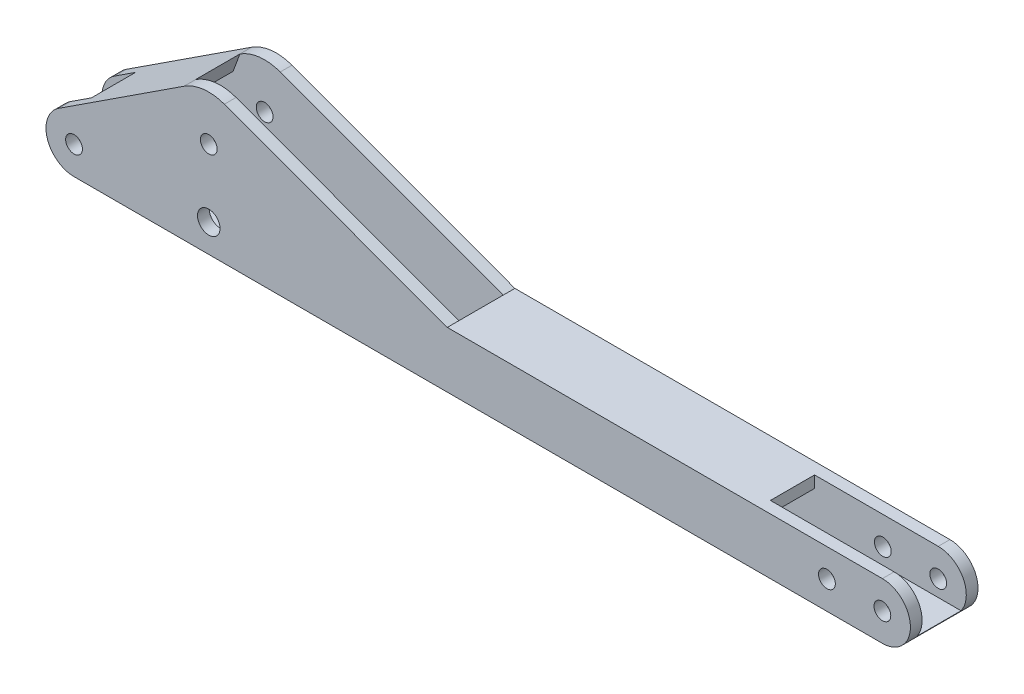
SolidWorks part; units mm, degrees
ref_plane "Front Plane" through (0, 0, 0) normal (0, 0, 1) x (1, 0, 0)
ref_plane "Top Plane" through (0, 0, 0) normal (0, 1, 0) x (1, 0, 0)
ref_plane "Right Plane" through (0, 0, 0) normal (1, 0, 0) x (0, 0, -1)
sketch "Sketch1" plane through (0, 0, 0) normal (0, 0, 1) x (1, 0, 0)
  line L0 (20.4249, 0) -> (3680.4249, 0)
  line L1 (-48.9901, 233.3512) -> (518.3771, 603.6692)
  line L2 (701.0552, 624.4483) -> (1710.4249, 254)
  line L3 (1710.4249, 254) -> (3680.4249, 254)
  arc A0 (20.4249, 0) -> (-48.9901, 233.3512) centre (20.4249, 127) cw
  arc A1 (518.3771, 603.6692) -> (701.0552, 624.4483) centre (630.4249, 432) cw
  circle A2 centre (20.4249, 127) radius 38
  circle A3 centre (630.4249, 127) radius 51
  circle A4 centre (630.4249, 432) radius 38
  arc A5 (3680.4249, 254) -> (3680.4249, 0) centre (3680.4249, 127) cw
  circle A6 centre (3680.4249, 127) radius 38
  circle A7 centre (3429.4249, 127) radius 38
  dimension "D2" = 127
  dimension "D3" = 76
  dimension "D4" = 102
  dimension "D5" = 76
  dimension "D8" = 205
  dimension "D6" = 305
  dimension "D7" = 127
  dimension "D9" = 254
  dimension "D10" = 251
  dimension "D11" = 1970
  dimension "D12" = 610
  dimension "D13" = 2799
extrude "Boss-Extrude1" add sketch "Sketch1" against normal blind 306
sketch "Sketch2" plane through (0, 254, 0) normal (0, 1, 0) x (1, 0, 0)
  line L0 (3680.4249, 306) -> (1710.4249, 306) construction
  line L1 (1710.4249, 306) -> (1710.4249, 0) construction
  line L2 (3120.4249, 306) -> (3680.4249, 306)
  line L3 (3120.4249, 306) -> (3120.4249, 0)
  line L4 (3120.4249, 0) -> (3680.4249, 0)
  line L5 (3680.4249, 306) -> (3680.4249, 0)
  line L6 (3807.4249, 0) -> (3807.4249, 306) construction
  line L7 (3680.4249, 253) -> (3807.4249, 253)
  line L8 (3680.4249, 253) -> (3680.4249, 53)
  line L9 (3680.4249, 53) -> (3807.4249, 53)
  line L10 (3807.4249, 253) -> (3807.4249, 53)
  line L17 (3120.4249, 253) -> (3680.4249, 253)
  line L18 (3120.4249, 53) -> (3680.4249, 53)
  dimension "D1" = 1410
  dimension "D2" = 53
  dimension "D3" = 53
sketch "Sketch3" plane through (0, 254, 0) normal (0, 1, 0) x (1, 0, 0)
sketch "Sketch8" plane through (285.1934, 777.0736, 0) normal (0.3445, 0.9388, 0) x (0.9388, -0.3445, 0)
  line L0 (278.6509, 253) -> (1518.1866, 253)
  line L1 (278.6509, 306) -> (1518.1866, 306)
  line L2 (278.6509, 306) -> (278.6509, 0)
  line L3 (278.6509, 0) -> (1518.1866, 0)
  line L4 (1518.1866, 306) -> (1518.1866, 0)
  line L5 (278.6509, 53) -> (1518.1866, 53)
  line M4 (442.9848, 306) -> (442.9848, 0)
  dimension "D1" = 53
  dimension "D2" = 53
extrude "Cut-Extrude5" cut sketch "Sketch8" against normal through all contours L5 L4 L0 M4 | L2 L5 L0 M4
sketch "Sketch9" plane through (0, 254, 0) normal (0, 1, 0) x (1, 0, 0)
extrude "Cut-Extrude10" cut sketch "Sketch2" against normal blind 201 contours L3 L18 L5 L17 | L10 L7 L5 L9
sketch "Sketch15" plane through (3120.4249, 0, 0) normal (1, 0, 0) x (0, 0, -1)
  line L0 (53, 201) -> (253, 201)
  line L1 (53, 254) -> (253, 254)
  line L2 (53, 254) -> (53, 53)
  line L3 (53, 53) -> (253, 53)
  line L4 (253, 254) -> (253, 53)
  line M3 (53, 254) -> (53, 53)
  line M4 (53, 53) -> (253, 53)
  line M5 (253, 53) -> (253, 254)
  dimension "D1" = 53
extrude "Cut-Extrude11" cut sketch "Sketch15" against normal through all contours L0 M3 M4 M5
sketch "Sketch16" plane through (0, 0, 0) normal (0, 0, 1) x (1, 0, 0)
  line L0 (-48.9901, 233.3512) -> (45.9249, 295.3017)
  line L1 (45.9249, 295.3017) -> (238.667, 0)
  line L2 (238.667, 0) -> (20.4249, 0)
  line L4 (20.4249, 0) -> (3680.4249, 0)
  line L5 (3680.4249, 254) -> (1710.4249, 254)
  line L6 (1710.4249, 254) -> (701.0552, 624.4483)
  line L7 (518.3771, 603.6692) -> (-48.9901, 233.3512)
  line L8 (20.4249, 0) -> (3680.4249, 0)
  line L9 (3680.4249, 254) -> (1710.4249, 254)
  line L10 (1710.4249, 254) -> (701.0552, 624.4483)
  line L11 (518.3771, 603.6692) -> (-48.9901, 233.3512)
  arc A3 (-48.9901, 233.3512) -> (20.4249, 0) centre (20.4249, 127) ccw
  arc A4 (3680.4249, 0) -> (3680.4249, 254) centre (3680.4249, 127) ccw
  arc A5 (701.0552, 624.4483) -> (518.3771, 603.6692) centre (630.4249, 432) ccw
  arc A6 (-48.9901, 233.3512) -> (20.4249, 0) centre (20.4249, 127) ccw
  arc A7 (3680.4249, 0) -> (3680.4249, 254) centre (3680.4249, 127) ccw
  arc A8 (701.0552, 624.4483) -> (518.3771, 603.6692) centre (630.4249, 432) ccw
  circle M12 centre (20.4249, 127) radius 38
  arc M13 (-48.9901, 233.3512) -> (20.4249, 0) centre (20.4249, 127) ccw
  line M14 (20.4249, 0) -> (3680.4249, 0)
  line M19 (518.3771, 603.6692) -> (-48.9901, 233.3512)
  dimension "D2" = 25.5
  dimension "D1" = 0
extrude "Cut-Extrude12" cut sketch "Sketch16" against normal blind 200 from offset 53 contours L1 M19 M13 M14 M12 offset against normal yes
sketch "Sketch18" plane through (167.3668, 109.2396, 0) normal (-0.8374, -0.5466, 0) x (0, 0, 1)
  line L0 (-53, 222.1875) -> (-53, 109.5764) construction
  line L1 (-253, -34.2374) -> (-53, -34.2374)
  line L2 (-253, -34.2374) -> (-253, 169.1875)
  line L3 (-253, 169.1875) -> (-53, 169.1875)
  line L4 (-53, -34.2374) -> (-53, 169.1875)
  line L5 (-253, 222.1875) -> (-53, 222.1875) construction
  dimension "D1" = 53
extrude "Cut-Extrude13" cut sketch "Sketch18" against normal through all
loft "Loft7" add section face at (1626.9302, 26.5, -153) section face at (306.5505, 26.5, -153)
